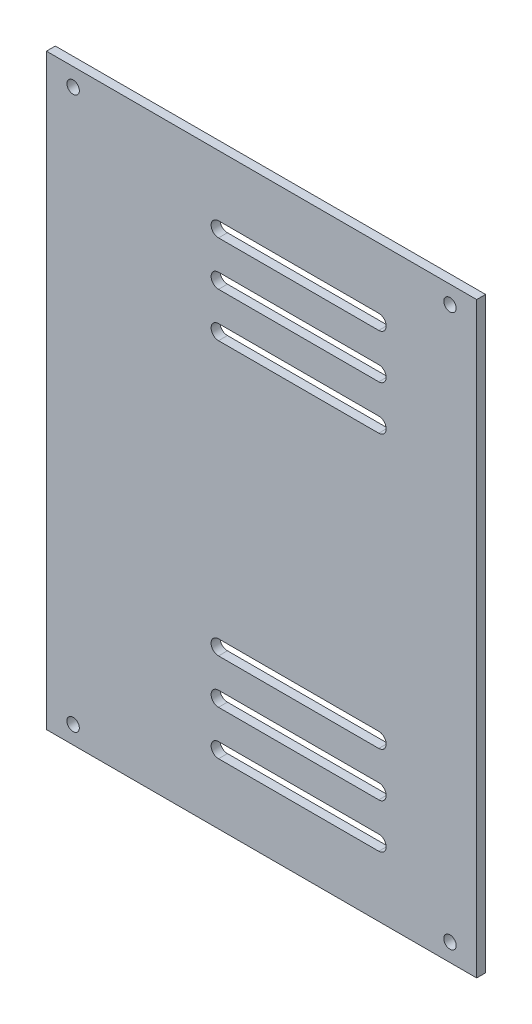
SolidWorks part; units mm, degrees
ref_plane "Front Plane" through (0, 0, 0) normal (0, 0, 1) x (1, 0, 0)
ref_plane "Top Plane" through (0, 0, 0) normal (0, 1, 0) x (1, 0, 0)
ref_plane "Right Plane" through (0, 0, 0) normal (1, 0, 0) x (0, 0, -1)
sketch "Service lid vents profile" plane through (0, 0, 0) normal (0, 0, 1) x (1, 0, 0)
  line L0 (-91, -99) -> (54, -99)
  line L1 (54, -99) -> (54, 99)
  line L2 (54, 99) -> (-91, 99)
  line L3 (-91, 99) -> (-91, -99)
  line L4 (-33, -78.5) -> (21, -78.5)
  line L5 (21, -73.5) -> (-33, -73.5)
  line L6 (-33, -63.5) -> (21, -63.5)
  line L7 (21, -58.5) -> (-33, -58.5)
  line L8 (-33, -48.5) -> (21, -48.5)
  line L9 (21, -43.5) -> (-33, -43.5)
  line L10 (-33, 43.5) -> (21, 43.5)
  line L11 (21, 48.5) -> (-33, 48.5)
  line L12 (-33, 58.5) -> (21, 58.5)
  line L13 (21, 63.5) -> (-33, 63.5)
  line L14 (-33, 73.5) -> (21, 73.5)
  line L15 (21, 78.5) -> (-33, 78.5)
  circle A0 centre (-82, -93) radius 2.1
  circle A1 centre (-82, 93) radius 2.1
  circle A2 centre (45, -93) radius 2.1
  circle A3 centre (45, 93) radius 2.1
  arc A4 (21, -78.5) -> (21, -73.5) centre (21, -76) ccw
  arc A5 (-33, -73.5) -> (-33, -78.5) centre (-33, -76) ccw
  arc A6 (21, -63.5) -> (21, -58.5) centre (21, -61) ccw
  arc A7 (-33, -58.5) -> (-33, -63.5) centre (-33, -61) ccw
  arc A8 (21, -48.5) -> (21, -43.5) centre (21, -46) ccw
  arc A9 (-33, -43.5) -> (-33, -48.5) centre (-33, -46) ccw
  arc A10 (21, 43.5) -> (21, 48.5) centre (21, 46) ccw
  arc A11 (-33, 48.5) -> (-33, 43.5) centre (-33, 46) ccw
  arc A12 (21, 58.5) -> (21, 63.5) centre (21, 61) ccw
  arc A13 (-33, 63.5) -> (-33, 58.5) centre (-33, 61) ccw
  arc A14 (21, 73.5) -> (21, 78.5) centre (21, 76) ccw
  arc A15 (-33, 78.5) -> (-33, 73.5) centre (-33, 76) ccw
extrude "Service lid vents" add sketch "Service lid vents profile" along normal blind 3
